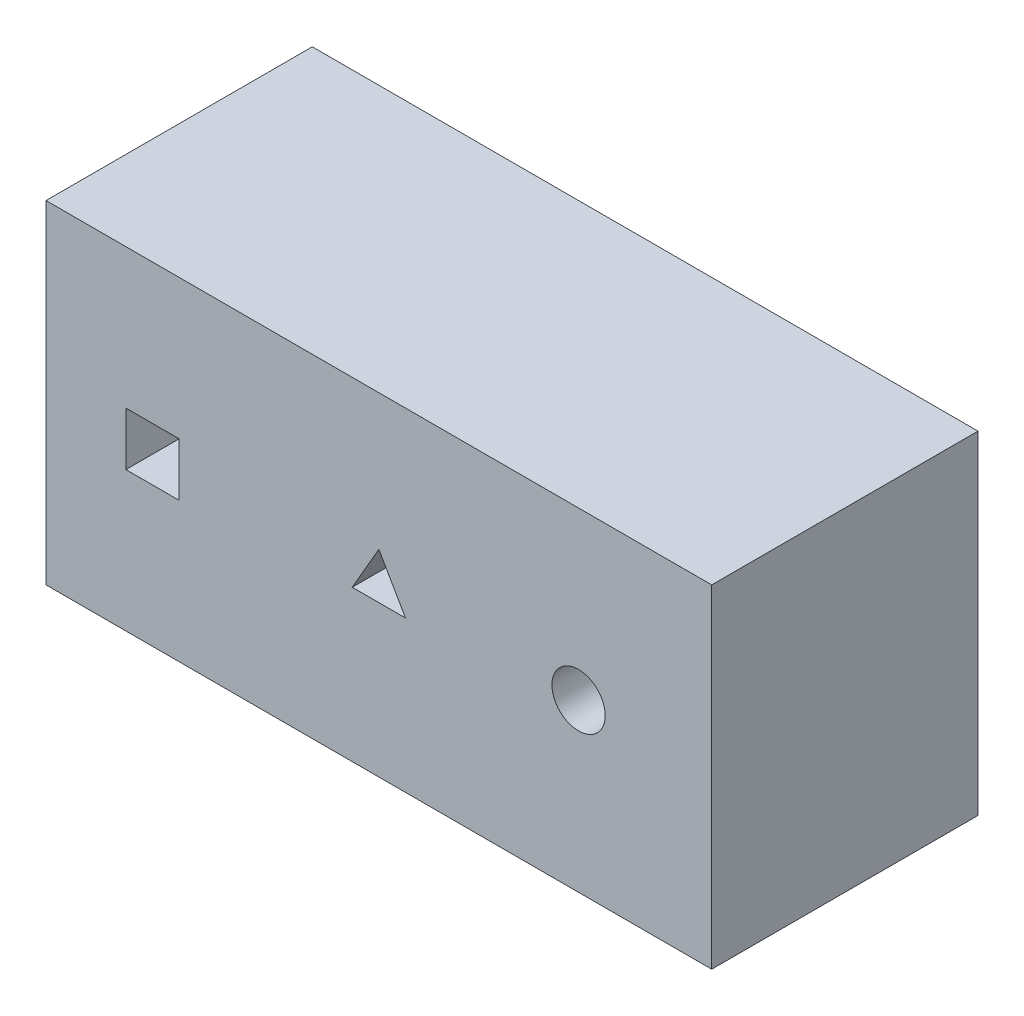
SolidWorks part; units mm, degrees
ref_plane "Front Plane" through (0, 0, 0) normal (0, 0, 1) x (1, 0, 0)
ref_plane "Top Plane" through (0, 0, 0) normal (0, 1, 0) x (1, 0, 0)
ref_plane "Right Plane" through (0, 0, 0) normal (1, 0, 0) x (0, 0, -1)
sketch "Sketch1" plane through (0, 0, 0) normal (0, 0, 1) x (1, 0, 0)
  line L1 (125, -62.5) -> (-125, -62.5)
  line L2 (125, -62.5) -> (125, 62.5)
  line L3 (125, 62.5) -> (-125, 62.5)
  line L4 (-125, -62.5) -> (-125, 62.5)
  line L5 (125, -62.5) -> (-125, 62.5) construction
  line L6 (125, 62.5) -> (-125, -62.5) construction
  line L7 (115, -57.5) -> (-115, -57.5)
  line L8 (115, -57.5) -> (115, 57.5)
  line L9 (115, 57.5) -> (-115, 57.5)
  line L10 (-115, -57.5) -> (-115, 57.5)
  line L11 (115, -57.5) -> (-115, 57.5) construction
  line L12 (115, 57.5) -> (-115, -57.5) construction
  point P0 (0, 0)
  point P6 (0, 0)
  dimension "D1" = 250
  dimension "D2" = 125
  dimension "D3" = 230
extrude "Boss-Extrude1" add sketch "Sketch1" along normal blind 100
sketch "Sketch2" plane through (0, 0, 0) normal (0, 0, -1) x (-1, 0, 0)
  line L1 (125, 62.5) -> (-125, 62.5)
  line L2 (125, 62.5) -> (125, -62.5)
  line L3 (125, -62.5) -> (-125, -62.5)
  line L4 (-125, 62.5) -> (-125, -62.5)
sketch "Sketch3" plane through (0, 0, 100) normal (0, 0, 1) x (1, 0, 0)
  line L0 (-125, 0) -> (125, 0) construction
  line L1 (-125, 62.5) -> (125, 62.5)
  line L2 (-125, 62.5) -> (-125, -62.5)
  line L3 (-125, -62.5) -> (125, -62.5)
  line L4 (125, 62.5) -> (125, -62.5)
  line L5 (0, 62.5) -> (0, -62.5) construction
  line L6 (-10, -5.7735) -> (0, 11.547)
  line L7 (-95, 10) -> (-75, 10)
  line L8 (-95, 10) -> (-95, -10)
  line L9 (-95, -10) -> (-75, -10)
  line L10 (-75, 10) -> (-75, -10)
  line L11 (-95, 10) -> (-75, -10) construction
  line L12 (-95, -10) -> (-75, 10) construction
  line L14 (-1.3522, 0) -> (0, -1.3522)
  line L18 (0, 11.547) -> (10, -5.7735)
  line L19 (10, -5.7735) -> (-10, -5.7735)
  line L20 (-10, -5.7735) -> (5, 2.8868) construction
  line L21 (10, -5.7735) -> (-5, 2.8868) construction
  line L22 (0, 11.547) -> (0, 0) construction
  circle A0 centre (75, 0) radius 10
  point P10 (-85, 0)
  point P20 (0, 0)
  point P27 (7.7505, -5.3087)
  point P28 (0, 0)
  line M21 (-125, 62.5) -> (-125, -62.5)
  line M22 (-125, -62.5) -> (125, -62.5)
  line M23 (125, -62.5) -> (125, 62.5)
  line M24 (125, 62.5) -> (-125, 62.5)
  line M25 (115, -57.5) -> (-115, -57.5)
  line M26 (-115, -57.5) -> (-115, 57.5)
  line M27 (-115, 57.5) -> (115, 57.5)
  line M28 (115, 57.5) -> (115, -57.5)
  dimension "D2" = 50
  dimension "cylinder" = 20
  dimension "D1" = 30
  dimension "square2" = 20
  dimension "square" = 20
  dimension "triangle3" = 20
  dimension "triangle2" = 20
  dimension "triangle" = 20
extrude "Boss-Extrude4" add sketch "Sketch3" against normal up to surface (100 mm away) contours A0 L7 L10 L9 L8 L18 L19 L6 M25 M28 M27 M26 | M24 M21 M22 M23 M28 M25 M26 M27 up to face at (0, 0, 0)
